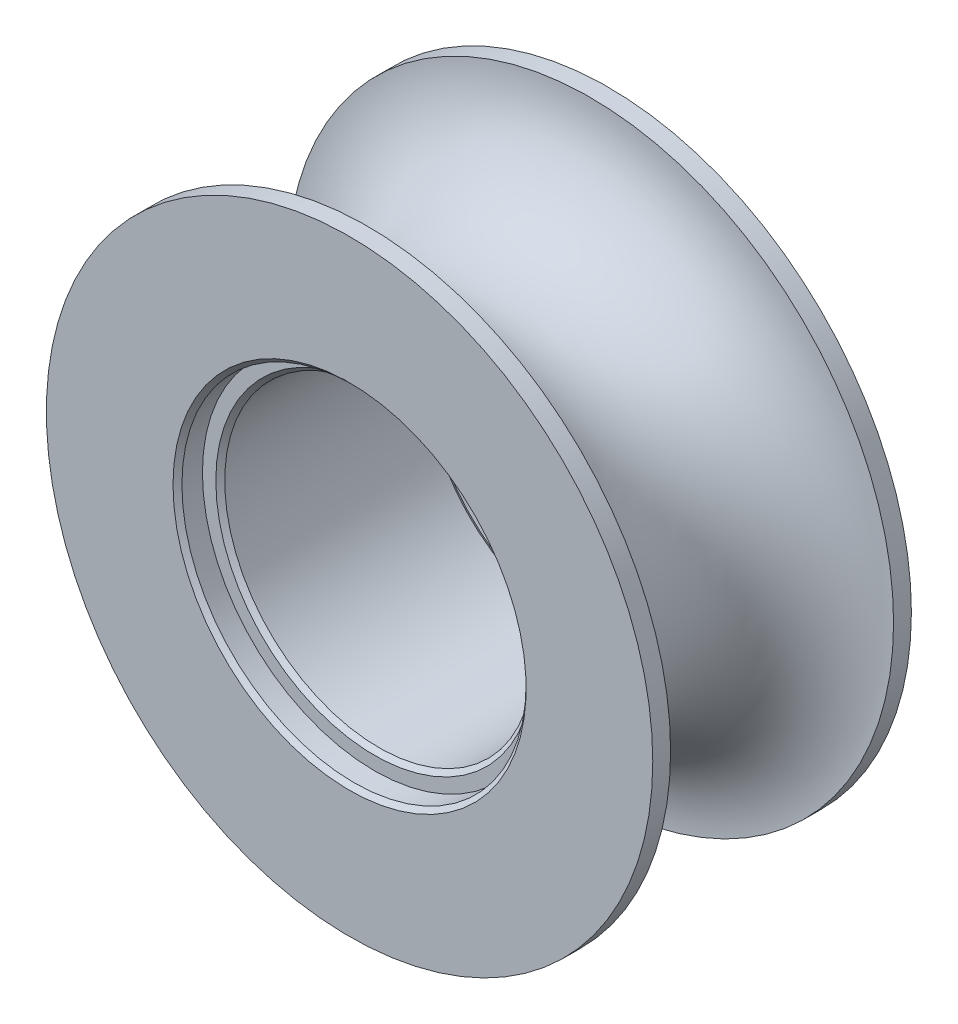
SolidWorks part; units mm, degrees
ref_plane "Front Plane" through (0, 0, 0) normal (0, 0, 1) x (1, 0, 0)
ref_plane "Top Plane" through (0, 0, 0) normal (0, 1, 0) x (1, 0, 0)
ref_plane "Right Plane" through (0, 0, 0) normal (1, 0, 0) x (0, 0, -1)
sketch "Sketch1" plane through (0, 0, 0) normal (1, 0, 0) x (0, 0, -1)
  line L0 (-64.981, 0) -> (67.5027, 0) construction
  line L1 (0, 57.2696) -> (0, -26.9167) construction
  line L2 (-6.25, 17) -> (-7.25, 17)
  line L3 (-7.25, 17) -> (-7.25, 8.65)
  line L4 (6.25, 17) -> (7.25, 17)
  line L5 (7.25, 17) -> (7.25, 8.65)
  line L7 (-7.25, 8.65) -> (7.25, 8.65)
  arc A0 (-6.25, 17) -> (6.25, 17) centre (0, 17) ccw
  dimension "D1" = 12.5
  dimension "D2" = 1
  dimension "D3" = 17
  dimension "D4" = 8.65
revolve "Revolve1" add sketch "Sketch1" angle 360 about L0
sketch "Sketch2" plane through (0, 0, -7.25) normal (0, 0, -1) x (-1, 0, 0)
  circle A0 centre (0, 0) radius 9.65
  dimension "D1" = 19.3
extrude "Cut-Extrude1" cut sketch "Sketch2" against normal blind 1.4
sketch "Sketch3" plane through (0, 0, 7.25) normal (0, 0, 1) x (1, 0, 0)
  circle A0 centre (0, 0) radius 9.65
  dimension "D1" = 19.3
extrude "Cut-Extrude2" cut sketch "Sketch3" against normal blind 1.4
chamfer "Chamfer1" distance 0.25 angle 45 4 edges at (9.65, 0, 7.25) (8.65, 0, 5.85) (-9.65, 0, -7.25) (-8.65, 0, -5.85)
